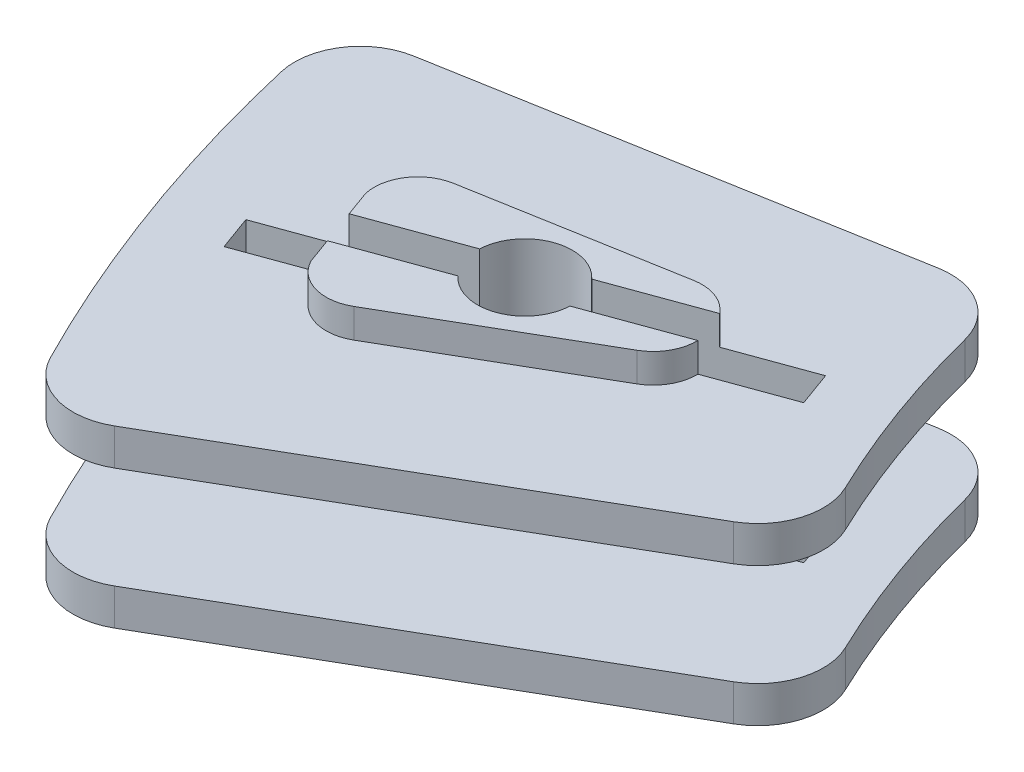
SolidWorks part; units mm, degrees
ref_plane "Front Plane" through (0, 0, 0) normal (0, 0, 1) x (1, 0, 0)
ref_plane "Top Plane" through (0, 0, 0) normal (0, 1, 0) x (1, 0, 0)
ref_plane "Right Plane" through (0, 0, 0) normal (1, 0, 0) x (0, 0, -1)
sketch "Sketch1" plane through (0, 0, 0) normal (0, 1, 0) x (1, 0, 0)
  line L0 (-0.3002, 0.1873) -> (-121.6087, -43.9654) construction
  line L1 (-0.3002, 0.1873) -> (-143.1552, -25.0019) construction
  line L2 (-0.3002, 0.1873) -> (-112.4354, -64.554) construction
  line L3 (-72.307, -13.5248) -> (-102.8964, -18.9186)
  line L4 (-64.2746, -35.5936) -> (-91.1745, -51.1242)
  line L5 (-2.7034, 0) -> (2.5073, 0) construction
  line L6 (0, 2.0352) -> (0, -1.7517) construction
  arc A0 (-97.4346, -49.2689) -> (-106.4993, -24.3638) centre (-0.3002, 0.1873) cw
  arc A1 (-72.307, -13.5248) -> (-67.1649, -16.8456) centre (-71.5256, -17.9565) cw
  arc A2 (-67.1649, -16.8456) -> (-62.4701, -29.7444) centre (-0.3002, 0.1873) ccw
  arc A3 (-62.4701, -29.7444) -> (-64.2746, -35.5936) centre (-66.5246, -31.6965) cw
  arc A4 (-97.4346, -49.2689) -> (-91.1745, -51.1242) centre (-93.4245, -47.2271) ccw
  arc A5 (-106.4993, -24.3638) -> (-102.8964, -18.9186) centre (-102.1149, -23.3502) cw
  dimension "D2" = 109
  dimension "D3" = 69
  dimension "D4" = 4.5
  dimension "D1" = 10
  dimension "D5" = 20
  dimension "D6" = 10
  dimension "D7" = 10
extrude "Boss-Extrude1" add sketch "Sketch1" along normal blind 2.5
sketch "Sketch2" plane through (0, 2.5, 0) normal (0, 1, 0) x (1, 0, 0)
  line L0 (-65.139, -23.4121) -> (-102.7267, -37.0929) construction
  line L1 (-75.6696, -26.6415) -> (-75.2938, -27.6739) construction
  line L4 (-75.9966, -24.2199) -> (-90.5443, -26.785)
  line L5 (-73.9756, -29.7724) -> (-86.7687, -37.1584)
  line L6 (-90.3897, -30.0554) -> (-88.7702, -34.5049) construction
  line L7 (-86.4226, -23.4121) -> (-80.5385, -39.5785) construction
  line L8 (-72.307, -13.5248) -> (-102.8964, -18.9186) construction
  arc A0 (-67.1649, -16.8456) -> (-62.4701, -29.7444) centre (-0.3002, 0.1873) ccw construction
  arc A1 (-106.4993, -24.3638) -> (-97.4346, -49.2689) centre (-0.3002, 0.1873) ccw construction
  arc A5 (-90.5443, -26.785) -> (-86.7687, -37.1584) centre (-89.571, -32.3046) ccw
  arc A6 (-73.9756, -29.7724) -> (-75.9966, -24.2199) centre (-75.4756, -27.1743) ccw
  point P17 (-83.9329, -30.2525)
  point P21 (-94.8378, -34.2215)
  point P22 (-72.6566, -26.1482)
  point P23 (-102.7267, -37.0929)
  point P25 (-65.139, -23.4121)
  dimension "D1" = 3
  dimension "D3" = 6
  dimension "D4" = 9
  dimension "D5" = 8
  dimension "D6" = 8.3953
extrude "Boss-Extrude2" add sketch "Sketch2" along normal blind 7
ref_plane "Plane1" through (0, 6, 0) normal (0, 1, 0) x (1, 0, 0)
mirror "Mirror1" about plane through (0, 6, 0) normal (0, 1, 0) of "Boss-Extrude1"
sketch "Sketch4" plane through (0, 12, 0) normal (0, 1, 0) x (1, 0, 0)
  line L0 (-65.139, -23.4121) -> (-102.7267, -37.0929) construction
  line L1 (-83.5264, -31.3692) -> (-84.4236, -28.9042) construction
  line L2 (-98.9256, -34.3792) -> (-87.1795, -30.1039)
  line L3 (-69.7952, -23.7765) -> (-81.5413, -28.0518)
  line L4 (-98.0706, -36.7284) -> (-86.3244, -32.4531)
  line L5 (-68.9401, -26.1258) -> (-80.6863, -30.401)
  line L6 (-98.9256, -34.3792) -> (-98.0706, -36.7284)
  line L7 (-69.7952, -23.7765) -> (-68.9401, -26.1258)
  arc A0 (-86.3244, -32.4531) -> (-80.6863, -30.401) centre (-83.9329, -30.2525) ccw
  arc A1 (-67.1649, -16.8456) -> (-62.4701, -29.7444) centre (-0.3002, 0.1873) ccw construction
  arc A2 (-106.4993, -24.3638) -> (-97.4346, -49.2689) centre (-0.3002, 0.1873) ccw construction
  arc A3 (-81.5413, -28.0518) -> (-87.1795, -30.1039) centre (-83.9329, -30.2525) ccw
  point P10 (-83.9329, -30.2525)
  point P13 (-102.7267, -37.0929)
  dimension "D1" = 6.5
  dimension "D2" = 12.5
  dimension "D3" = 2.5
extrude "Cut-Extrude1" cut sketch "Sketch4" against normal through all
sketch "Sketch5" plane through (0, 12, 0) normal (0, 1, 0) x (1, 0, 0)
  line L0 (-88.0702, -37.8288) -> (-75.7588, -30.7209)
  line L1 (-77.9722, -24.6395) -> (-91.9722, -27.108)
  line L6 (-102.7267, -37.0929) -> (-65.139, -23.4121) construction
  line L8 (-94.3765, -30.7281) -> (-93.7352, -32.49)
  line L9 (-77.6528, -27.0403) -> (-77.052, -28.691) construction
  line L10 (-89.2596, -36.084) -> (-91.7507, -29.2397) construction
  line L15 (-80.6863, -30.401) -> (-68.9401, -26.1258) construction
  line L16 (-69.7952, -23.7765) -> (-81.5413, -28.0518) construction
  line L21 (-80.6863, -30.401) -> (-74.2594, -28.0618)
  line L22 (-75.1144, -25.7126) -> (-81.5413, -28.0518)
  line L23 (-93.7352, -32.49) -> (-93.3077, -33.6646) construction
  line L24 (-92.8802, -34.8392) -> (-92.2389, -36.6012)
  line L25 (-93.3077, -33.6646) -> (-92.8802, -34.8392) construction
  line L26 (-69.7952, -23.7765) -> (-75.1144, -25.7126) construction
  line L28 (-74.2594, -28.0618) -> (-68.9401, -26.1258) construction
  line L29 (-92.8802, -34.8392) -> (-86.3244, -32.4531)
  line L30 (-93.7352, -32.49) -> (-87.1795, -30.1039)
  arc A18 (-106.4993, -24.3638) -> (-97.4346, -49.2689) centre (-0.3002, 0.1873) ccw construction
  arc A19 (-67.1649, -16.8456) -> (-62.4701, -29.7444) centre (-0.3002, 0.1873) ccw construction
  arc A20 (-75.1144, -25.7126) -> (-77.9722, -24.6395) centre (-77.4513, -27.5939) ccw
  arc A21 (-74.2594, -28.0618) -> (-75.7588, -30.7209) centre (-77.2588, -28.1228) cw
  arc A22 (-88.0702, -37.8288) -> (-92.2389, -36.6012) centre (-89.5702, -35.2308) cw
  arc A23 (-94.3765, -30.7281) -> (-91.9722, -27.108) centre (-91.4513, -30.0625) cw
  arc A24 (-86.3244, -32.4531) -> (-80.6863, -30.401) centre (-83.9329, -30.2525) ccw construction
  arc A25 (-81.5413, -28.0518) -> (-87.1795, -30.1039) centre (-83.9329, -30.2525) ccw construction
  arc A26 (-86.3244, -32.4531) -> (-80.6863, -30.401) centre (-83.9329, -30.2525) ccw
  arc A27 (-81.5413, -28.0518) -> (-87.1795, -30.1039) centre (-83.9329, -30.2525) ccw
  dimension "D2" = 3
  dimension "D1" = 10
  dimension "D3" = 5.5
  dimension "D4" = 14
  dimension "D5" = 6.25
  dimension "D8" = 10.0235
extrude "Boss-Extrude3" add sketch "Sketch5" along normal blind 2
